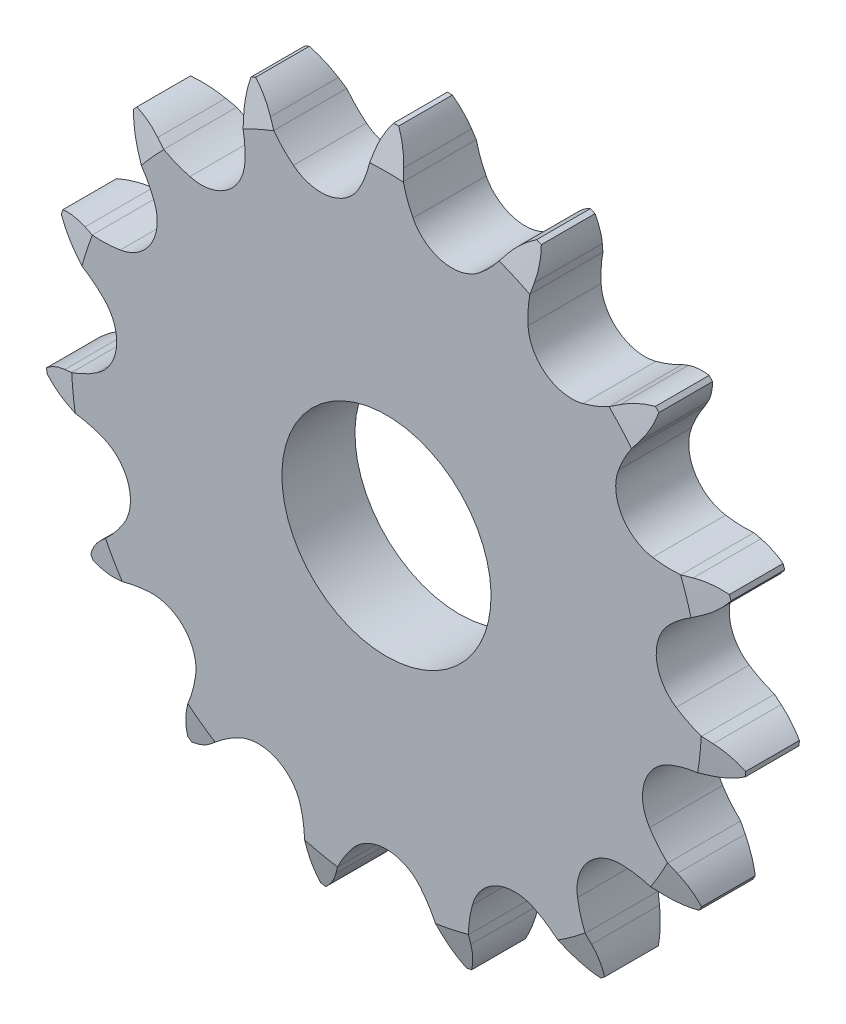
SolidWorks part; units mm, degrees
other "Markup1"
sketch "Sketch8" plane through (25.4057, 25.527, 2.655) normal (0.077, 0.203, 0.9761) x (0.9715, 0.2049, -0.1192)
ref_plane "Front Plane" through (0, 0, 0) normal (0, 0, 1) x (1, 0, 0)
ref_plane "Top Plane" through (0, 0, 0) normal (0, 1, 0) x (1, 0, 0)
ref_plane "Right Plane" through (0, 0, 0) normal (1, 0, 0) x (0, 0, -1)
sketch "Sketch1" plane through (0, 0, 0) normal (0, 0, 1) x (1, 0, 0)
  line L3 (0, 0) -> (0, 4.5813) construction
  line L4 (-2.2906, 22.9064) -> (2.2906, 22.9064) construction
  line L5 (3.9479, 4.5813) -> (3.9479, 0) construction
  line L6 (-2.2906, 26.1033) -> (2.2906, 26.1033) construction
  line L7 (3.9479, 26.1033) -> (0.3876, 23.2202) construction
  line L8 (3.9479, 26.1033) -> (-3.5656, 22.6422) construction
  line L9 (-3.5656, 22.6422) -> (-5.4824, 26.8032) construction
  line L10 (-8.6957, 4.5813) -> (-8.6957, 0) construction
  line L11 (-2.2906, 21.058) -> (2.2906, 21.058) construction
  line L12 (0, 0) -> (-0.9525, 4.4812) construction
  line L13 (-3.5656, 22.6422) -> (-3.8617, 23.2849) construction
  line L14 (3.5656, 22.6422) -> (3.8617, 23.2849) construction
  line L59 (0, 0) -> (0, -15) construction
  line L60 (-5, -25.527) -> (5, -25.527) construction
  circle A0 centre (0, 0) radius 7.6 construction
  circle A2 centre (0, 0) radius 25.527 construction
  circle A8 centre (0, 0) radius 22.9064 construction
  circle A9 centre (0, 22.9064) radius 3.1781 construction
  arc A10 (-3.5656, 22.6422) -> (-2.4698, 20.9063) centre (3.9234, 26.1559) ccw construction
  circle A11 centre (-8.6957, 21.058) radius 5.3223 construction
  arc A12 (2.4698, 20.9063) -> (-2.4698, 20.9063) centre (0, 22.9064) cw construction
  arc A13 (-2.4698, 20.9063) -> (-3.5656, 22.6422) centre (3.9234, 26.1559) cw construction
  arc A14 (-3.8617, 23.2849) -> (-5.357, 25.2029) centre (-8.6957, 21.058) ccw construction
  arc A15 (2.4698, 20.9063) -> (3.5656, 22.6422) centre (-3.9234, 26.1559) ccw construction
  arc A16 (3.8617, 23.2849) -> (5.357, 25.2029) centre (8.6957, 21.058) cw construction
  arc A127 (-5.357, 25.2029) -> (5.357, 25.2029) centre (0, 22.9064) cw construction
  point P3 (0, 22.9064)
  point P7 (0, 21.058)
  point P11 (0, -25.527)
  point P24 (3.9479, 26.1033)
  point P27 (0, 22.9064)
  point P38 (-5.357, 25.2029)
  point P50 (0, 26.1033)
  dimension "For Shaft Diameter" = 15.2
  dimension "No. of Teeth" = 15
  dimension "D3" = 4.5813
  dimension "Pitch" = 10
sketch "Sketch2" plane through (0, 0, 0) normal (1, 0, 0) x (0, 0, -1)
  line L1 (-2.655, 7.6) -> (2.655, 7.6) construction
  line L3 (-2.655, -25.527) -> (2.655, -25.527) construction
  line L4 (-2.655, 25.527) -> (2.655, 25.527) construction
  line L11 (-2.655, 0) -> (2.655, 0) construction
  point P4 (0, 7.6)
  point P6 (0, 25.527)
  point P10 (0, -25.527)
  point P14 (0, 0)
  dimension "O'all Width" = 5.31
sketch "Sketch3" plane through (0, 0, 0) normal (1, 0, 0) x (0, 0, -1)
  line L0 (-2.655, 25.527) -> (2.655, 25.527) construction
  line L1 (-2.655, 7.6) -> (2.655, 7.6)
  line L2 (-2.655, 7.6) -> (-2.655, 25.527)
  line L3 (-2.655, 25.527) -> (2.655, 25.527)
  line L4 (2.655, 7.6) -> (2.655, 25.527)
  line L5 (-2.655, 7.6) -> (2.655, 7.6) construction
revolve "Revolve5" add sketch "Sketch3" angle 360 about L11
sketch "Sketch4" plane through (0, 0, 0) normal (0, 0, 1) x (1, 0, 0)
  line L0 (-3.5656, 22.6422) -> (-3.8617, 23.2849) construction
  line L1 (1.2199, 22.8887) -> (1.0639, 23.5789)
  line L2 (-3.5656, 22.6422) -> (-3.8617, 23.2849) construction
  line L4 (3.5656, 22.6422) -> (3.8617, 23.2849) construction
  line L5 (3.5656, 22.6422) -> (3.8617, 23.2849) construction
  line L6 (0, 0) -> (0, 25.527) construction
  line L9 (8.1953, 21.4061) -> (8.6185, 21.9731)
  line L10 (0, 0) -> (4.7625, 22.4058) construction
  line L11 (0, 0) -> (-4.7625, 22.4058) construction
  arc A0 (-3.8617, 23.2849) -> (-5.357, 25.2029) centre (-8.6957, 21.058) ccw construction
  arc A1 (-3.5656, 22.6422) -> (-2.4698, 20.9063) centre (3.9234, 26.1559) ccw construction
  arc A2 (-2.4698, 20.9063) -> (2.4698, 20.9063) centre (0, 22.9064) ccw construction
  circle A3 centre (0, 0) radius 25.527 construction
  arc A6 (-3.8617, 23.2849) -> (-5.357, 25.2029) centre (-8.6957, 21.058) ccw construction
  arc A7 (-3.5656, 22.6422) -> (-2.4698, 20.9063) centre (3.9234, 26.1559) ccw construction
  arc A8 (-2.4698, 20.9063) -> (2.4698, 20.9063) centre (0, 22.9064) ccw construction
  arc A12 (2.4698, 20.9063) -> (3.5656, 22.6422) centre (-3.9234, 26.1559) ccw construction
  arc A13 (5.357, 25.2029) -> (3.8617, 23.2849) centre (8.6957, 21.058) ccw construction
  arc A14 (5.357, 25.2029) -> (-5.357, 25.2029) centre (0, 22.9064) ccw construction
  arc A15 (2.4698, 20.9063) -> (3.5656, 22.6422) centre (-3.9234, 26.1559) ccw construction
  arc A16 (5.357, 25.2029) -> (3.8617, 23.2849) centre (8.6957, 21.058) ccw construction
  arc A17 (5.357, 25.2029) -> (-5.357, 25.2029) centre (0, 22.9064) ccw construction
  arc A23 (10.48, 23.5384) -> (0, 25.766) centre (4.7625, 22.4058) ccw
  arc A24 (1.0639, 23.5789) -> (0, 25.766) centre (-4.1275, 22.4058) ccw
  arc A25 (1.2199, 22.8887) -> (1.9308, 20.963) centre (9.2758, 24.7686) ccw
  arc A26 (1.9308, 20.963) -> (6.7625, 19.936) centre (4.7625, 22.4058) ccw
  arc A27 (6.7625, 19.936) -> (8.1953, 21.4061) centre (1.6004, 26.4001) ccw
  arc A28 (10.48, 23.5384) -> (8.6185, 21.9731) centre (12.8839, 18.7899) ccw
  circle A29 centre (0, 0) radius 22.9064 construction
  circle A30 centre (0, 0) radius 17.0778 construction
  dimension "D2" = 12
  dimension "D1" = 12
  dimension "D5" = 24.733
  dimension "D3" = 2
extrude "Cut-Extrude4" cut sketch "Sketch4" against normal through all both and the other way through all
pattern_circular "CirPattern2" count 15 over 360 about axis through (0, 0, 0) along (0, 0, 1) of "Cut-Extrude4"
sketch "Sketch5" plane through (0, 0, 2.655) normal (0, 0, 1) x (1, 0, 0)
  circle A0 centre (0, 0) radius 22.9064 construction
  circle A1 centre (0, 0) radius 22.9064
extrude "Cut-Extrude5" cut sketch "Sketch5" against normal through all draft 75 flip side to cut
sketch "Sketch6" plane through (0, 0, -2.655) normal (0, 0, -1) x (-1, 0, 0)
  circle A1 centre (0, 0) radius 22.9064
  circle A2 centre (0, 0) radius 22.9064
  dimension "D1" = 0
extrude "Cut-Extrude6" cut sketch "Sketch6" against normal through all draft 75 flip side to cut
sketch "Sketch7" plane through (0, 0, 0) normal (0, 0, 1) x (1, 0, 0)
  point P0 (4.7625, 22.4058)
  point P1 (-4.7625, 22.4058)
equation "\"D1@Sketch1\"=\"E@Sketch1\""
equation "\"No. of Teeth@CirPattern2\"=\"No. of Teeth@Sketch1\""
equation "\"D2@Sketch4\" =  ( 360 / \"No. of Teeth@Sketch1\" )  * .5"
equation "\"D1@Sketch4\" = \"D2@Sketch4\""
equation "\"D5@Sketch4\"=\"D4@Sketch4\""
equation "\"D3@Sketch1\"=\"PD@Sketch1\"*.1"
